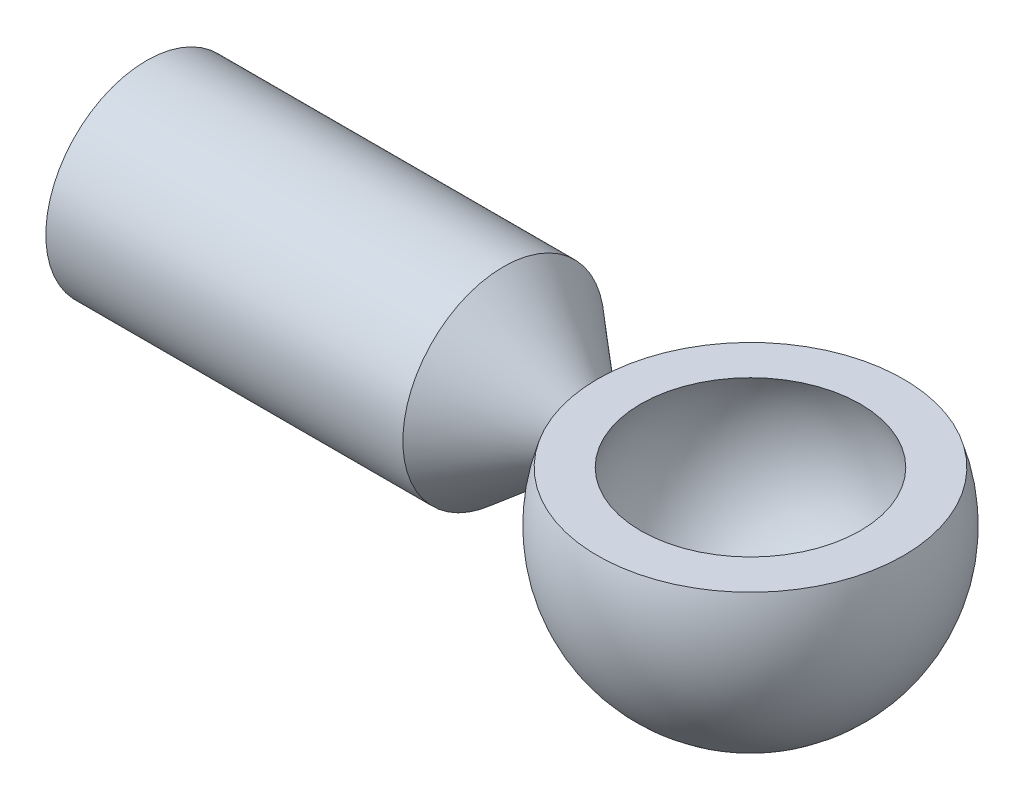
SolidWorks part; units mm, degrees
ref_plane "前视基准面" through (0, 0, 0) normal (0, 0, 1) x (1, 0, 0)
ref_plane "上视基准面" through (0, 0, 0) normal (0, 1, 0) x (1, 0, 0)
ref_plane "右视基准面" through (0, 0, 0) normal (1, 0, 0) x (0, 0, -1)
sketch "草图1" plane through (0, 0, 0) normal (0, 0, 1) x (1, 0, 0)
  line L0 (-24.0779, 0) -> (0, 0) construction
  line L1 (0, 0) -> (0, 28.0909) construction
  line L2 (-5.4544, 2.5) -> (-7.5993, 2.5)
  line L3 (0, 0) -> (0, -8) construction
  line L4 (0, -6) -> (0, -8)
  arc A0 (-7.5993, 2.5) -> (0, -8) centre (0, 0) ccw
  arc A1 (-5.4544, 2.5) -> (0, -6) centre (0, 0) ccw
  dimension "D1" = 16
  dimension "D2" = 12
  dimension "D3" = 2.5
revolve "旋转1" add sketch "草图1" angle 360 about L3
sketch "草图2" plane through (0, 0, 0) normal (0, 0, 1) x (1, 0, 0)
  line L0 (0, 10.1782) -> (0, 0) construction
  line L1 (0, 0) -> (-32.7573, 0) construction
  line L2 (-7.5, 0) -> (-7.5, 1)
  line L3 (-7.5, 1) -> (-12.267, 5)
  line L4 (-12.267, 5) -> (-30, 5)
  line L5 (-30, 5) -> (-30, 0)
  line L6 (-7.5, 0) -> (-30, 0)
  point P6 (-16.2081, 0)
  point P10 (0, 0)
  point P11 (-7.4215, 0.8983)
  point P12 (-32.7573, 0)
  point P13 (-9.2521, 2.4194)
  point P14 (-12.9414, 5)
  dimension "D1" = 30
  dimension "D2" = 7.5
  dimension "D3" = 1
  dimension "D4" = 5
  dimension "D5" = 40
revolve "旋转2" add sketch "草图2" angle 360 about L6
sketch "草图4" plane through (-30, 0, 0) normal (-1, 0, 0) x (0, 0, 1)
  circle A0 centre (0, 0) radius 3
  dimension "D1" = 6
extrude "切除-拉伸1" cut sketch "草图4" against normal blind 15
